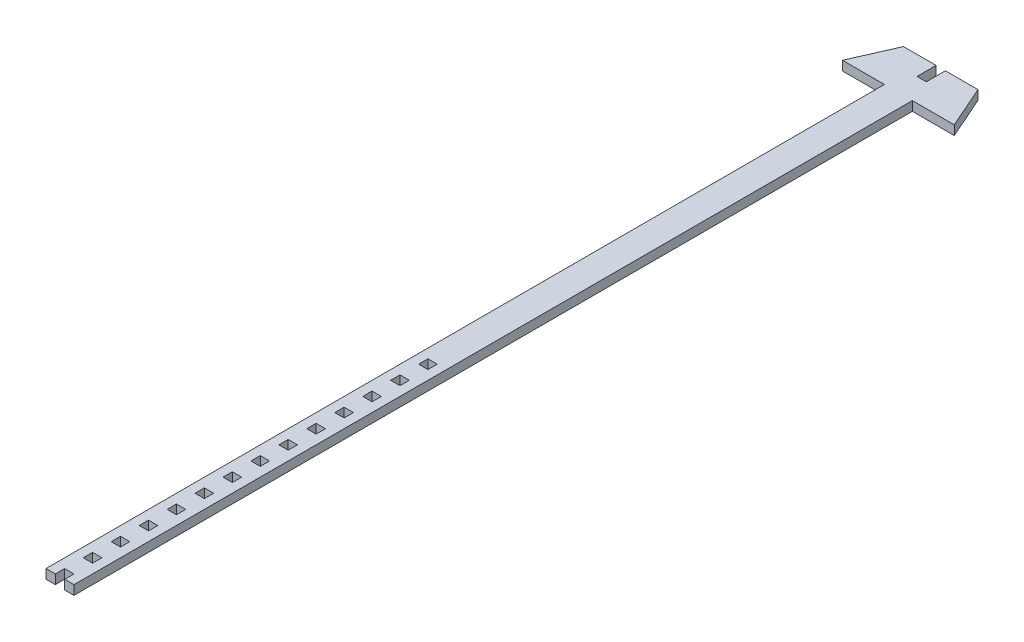
SolidWorks part; units mm, degrees
ref_plane "Спереди" through (0, 0, 0) normal (0, 0, 1) x (1, 0, 0)
ref_plane "Сверху" through (0, 0, 0) normal (0, 1, 0) x (1, 0, 0)
ref_plane "Справа" through (0, 0, 0) normal (1, 0, 0) x (0, 0, -1)
sketch "Эскиз1" plane through (0, 0, 0) normal (0, 1, 0) x (1, 0, 0)
  line L0 (-60, 0) -> (-15, 0)
  line L1 (-40, 45.4615) -> (-5, 45.4615)
  line L2 (-40, 45.4615) -> (-60, 0)
  line L3 (60, 0) -> (40, 45.4615)
  line L4 (0, 22.7308) -> (-30, 22.7308) construction
  line L5 (30, 22.7308) -> (0, 22.7308) construction
  line L6 (15, 0) -> (60, 0)
  line L7 (-5, 25) -> (-5, 45.4615)
  line L8 (15, 0) -> (15, -900)
  line L9 (5, 25) -> (-5, 25)
  line L10 (-15, 0) -> (-15, -900)
  line L11 (5, 25) -> (5, 45.4615)
  line L12 (5, -900) -> (15, -900)
  line L13 (5, 45.4615) -> (40, 45.4615)
  line L14 (-15, -900) -> (-5, -900)
  line L15 (-5, -870) -> (-5, -860)
  line L16 (5, -900) -> (5, -890)
  line L17 (5, -890) -> (-5, -890)
  line L18 (-5, -900) -> (-5, -890)
  line L19 (5, -860) -> (-5, -860)
  line L20 (5, -870) -> (5, -860)
  line L21 (-5, -840) -> (-5, -830)
  line L22 (5, -830) -> (-5, -830)
  line L23 (5, -840) -> (5, -830)
  line L24 (5, -870) -> (-5, -870)
  line L25 (-5, -840) -> (5, -840)
  line L26 (-5, -810) -> (-5, -800)
  line L27 (5, -800) -> (-5, -800)
  line L28 (5, -810) -> (5, -800)
  line L29 (-5, -810) -> (5, -810)
  line L30 (-5, -780) -> (-5, -770)
  line L31 (5, -770) -> (-5, -770)
  line L32 (5, -780) -> (5, -770)
  line L33 (-5, -780) -> (5, -780)
  line L34 (-5, -750) -> (-5, -740)
  line L35 (5, -740) -> (-5, -740)
  line L36 (5, -750) -> (5, -740)
  line L37 (-5, -750) -> (5, -750)
  line L38 (-5, -720) -> (-5, -710)
  line L39 (5, -710) -> (-5, -710)
  line L40 (5, -720) -> (5, -710)
  line L41 (-5, -720) -> (5, -720)
  line L42 (-5, -690) -> (-5, -680)
  line L43 (5, -680) -> (-5, -680)
  line L44 (5, -690) -> (5, -680)
  line L45 (-5, -690) -> (5, -690)
  line L46 (-5, -660) -> (-5, -650)
  line L47 (5, -650) -> (-5, -650)
  line L48 (5, -660) -> (5, -650)
  line L49 (-5, -660) -> (5, -660)
  line L50 (-5, -630) -> (-5, -620)
  line L51 (5, -620) -> (-5, -620)
  line L52 (5, -630) -> (5, -620)
  line L53 (-5, -630) -> (5, -630)
  line L54 (-5, -600) -> (-5, -590)
  line L55 (5, -590) -> (-5, -590)
  line L56 (5, -600) -> (5, -590)
  line L57 (-5, -600) -> (5, -600)
  line L58 (-5, -570) -> (-5, -560)
  line L59 (5, -560) -> (-5, -560)
  line L60 (5, -570) -> (5, -560)
  line L61 (-5, -570) -> (5, -570)
  line L62 (-5, -540) -> (-5, -530)
  line L63 (5, -530) -> (-5, -530)
  line L64 (5, -540) -> (5, -530)
  line L65 (-5, -540) -> (5, -540)
  line L66 (-5, -510) -> (-5, -500)
  line L67 (5, -500) -> (-5, -500)
  line L68 (5, -510) -> (5, -500)
  line L69 (-5, -510) -> (5, -510)
  point P12 (0, 25)
  point P13 (0, 0)
  point P18 (0, -700)
  point P20 (0, 0)
  dimension "D3" = 10
  dimension "D4" = 900
  dimension "D5" = 15
  dimension "D1" = 120
  dimension "D2" = 80
  dimension "D6" = 30
  dimension "D7" = 25
  dimension "D8" = 15
  dimension "D9" = 10
  dimension "D10" = 10
  dimension "D11" = 3
  dimension "D12" = 12
extrude "Бобышка-Вытянуть1" add sketch "Эскиз1" along normal blind 10
